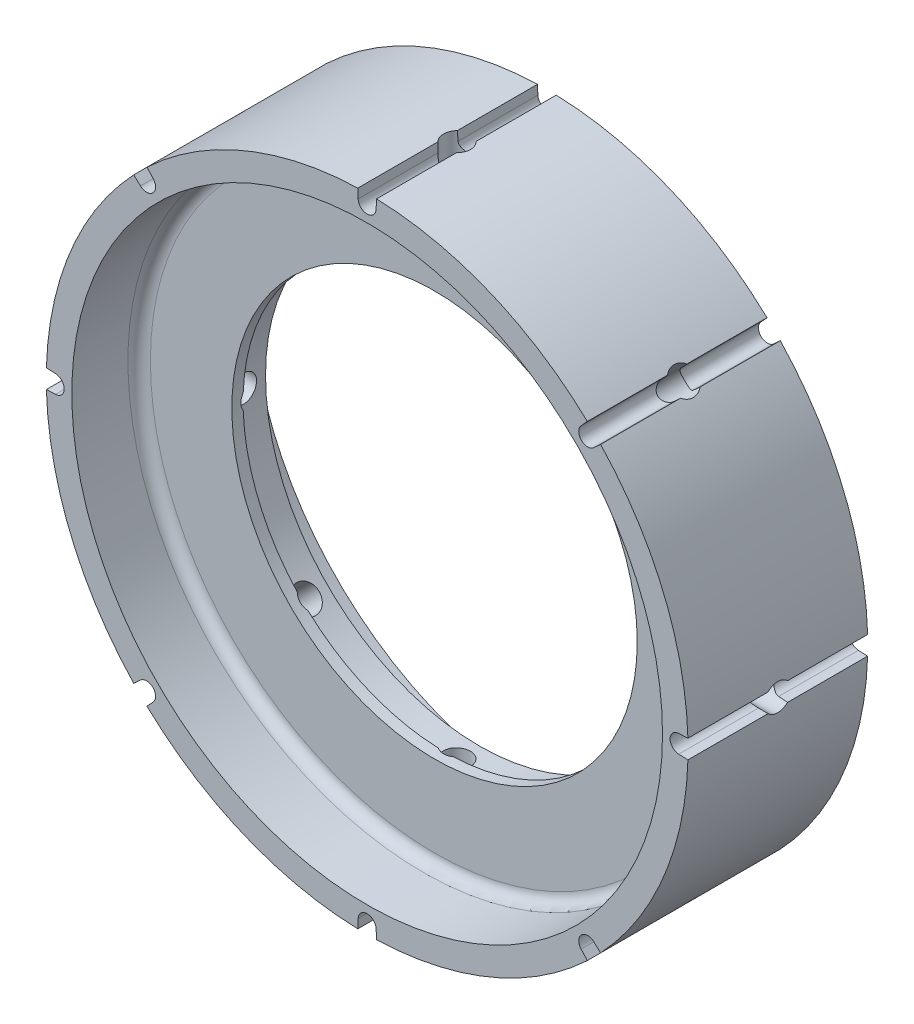
SolidWorks part; units mm, degrees
ref_plane "Front Plane" through (0, 0, 0) normal (0, 0, 1) x (1, 0, 0)
ref_plane "Top Plane" through (0, 0, 0) normal (0, 1, 0) x (1, 0, 0)
ref_plane "Right Plane" through (0, 0, 0) normal (1, 0, 0) x (0, 0, -1)
sketch "Sketch1" plane through (0, 0, 0) normal (0, 0, 1) x (1, 0, 0)
  circle A4 centre (0, 0) radius 14.2875
  circle A5 centre (0, 0) radius 13.15
  circle A6 centre (0, 0) radius 13.15
  dimension "D1" = 0.15
  dimension "D3" = 1.1375
  dimension "D2" = 28.575
extrude "Boss-Extrude1" add sketch "Sketch1" against normal blind 3
sketch "Sketch2" plane through (0, 0, 0) normal (0, 0, 1) x (1, 0, 0)
  circle A0 centre (0, 0) radius 14.2875
  circle A1 centre (0, 0) radius 9.025
  circle A2 centre (0, 0) radius 14.2875 construction
  dimension "D1" = 18.05
extrude "Boss-Extrude2" add sketch "Sketch2" along normal blind 2
sketch "Sketch3" plane through (0, 0, 2) normal (0, 0, 1) x (1, 0, 0)
  circle A0 centre (0, 0) radius 13.15 construction
  circle A1 centre (0, 0) radius 14.2875
  circle A2 centre (0, 0) radius 14.2875
  circle A3 centre (0, 0) radius 13.15
  dimension "D1" = 0
extrude "Boss-Extrude3" add sketch "Sketch3" along normal blind 3
fillet "Fillet1" radius 0.5 2 edges at (13.15, 0, 2) (13.15, 0, 0)
sketch "Sketch4" plane through (0, 0, 0) normal (0, 0, -1) x (-1, 0, 0)
  circle A1 centre (0, 0) radius 9.525
extrude "Cut-Extrude2" cut sketch "Sketch4" against normal blind 1.5
sketch "Sketch5" plane through (0, 0, -3) normal (0, 0, -1) x (-1, 0, 0)
  line L0 (-13.8709, 0.3997) -> (-14.2814, 0.4167)
  line L1 (-13.8709, -0.3997) -> (-14.2814, -0.4167)
  circle A3 centre (0, 0) radius 14.2875 construction
  circle A5 centre (0, 0) radius 14.2875
  circle A6 centre (-13.8875, 0) radius 0.4
  circle M4 centre (0, 0) radius 14.2875
extrude "Cut-Extrude4" cut sketch "Sketch5" against normal through all contours A6 | A6 L0 M4 | A6 A5 L1
ref_plane "Plane1" through (14.2814, 0, 0) normal (1, 0, 0) x (0, 0, -1)
sketch "Sketch6" plane through (14.2814, 0, 0) normal (1, 0, 0) x (0, 0, -1)
  line L0 (-5, 0.4167) -> (3, 0.4167) construction
  line L1 (-5, 0.4167) -> (3, 0.4167)
  circle A0 centre (-1, 0) radius 0.6
extrude "Cut-Extrude5" cut sketch "Sketch6" against normal blind 10 contours L1 A0 | L1 A0
sketch "Sketch7" plane through (0, 0, 0) normal (0, 1, 0) x (1, 0, 0)
  line L0 (0, 0) -> (0, 6.608) construction
pattern_circular "CirPattern1" count 8 over 360 about axis through (0, 0, 0) along (0, 0, 1) of "Cut-Extrude5", "Cut-Extrude4"
